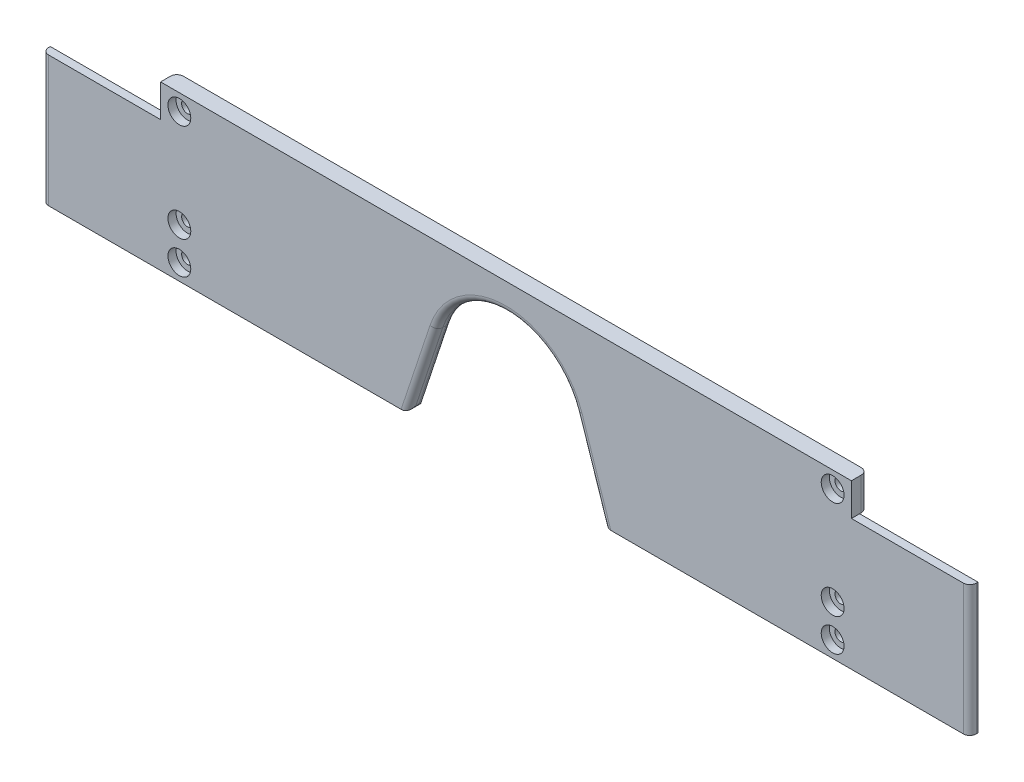
SolidWorks part; units mm, degrees
ref_plane "Front Plane" through (0, 0, 0) normal (0, 0, 1) x (1, 0, 0)
ref_plane "Top Plane" through (0, 0, 0) normal (0, 1, 0) x (1, 0, 0)
ref_plane "Right Plane" through (0, 0, 0) normal (1, 0, 0) x (0, 0, -1)
sketch "Sketch1" plane through (0, 0, 0) normal (0, 0, 1) x (1, 0, 0)
  line L0 (0, 31.75) -> (0, -31.75) construction
  line L1 (-134.3025, -31.75) -> (134.3025, -31.75)
  line L2 (-134.3025, -31.75) -> (-134.3025, 31.75)
  line L3 (-134.3025, 31.75) -> (134.3025, 31.75)
  line L4 (134.3025, -31.75) -> (134.3025, 31.75)
  line L5 (-134.3025, -31.75) -> (134.3025, 31.75) construction
  line L6 (-134.3025, 31.75) -> (134.3025, -31.75) construction
  circle A0 centre (-127, 25.4) radius 2.286
  circle A1 centre (-127, -12.7) radius 2.286
  circle A2 centre (-127, -25.4) radius 2.286
  circle A3 centre (-127, -25.4) radius 2.286 construction
  circle A4 centre (127, 25.4) radius 2.286
  circle A5 centre (127, -12.7) radius 2.286
  circle A6 centre (127, -25.4) radius 2.286
  point P0 (0, 0)
  dimension "D1" = 63.5
  dimension "D2" = 268.605
extrude "Boss-Extrude1" add sketch "Sketch1" along normal blind 3.175
sketch "Sketch2" plane through (0, 0, 3.175) normal (0, 0, 1) x (1, 0, 0)
  line L0 (134.3025, 31.75) -> (-134.3025, 31.75) construction
  line L1 (-180.34, -31.75) -> (180.34, -31.75)
  line L2 (-180.34, -31.75) -> (-180.34, 31.75)
  line L3 (-180.34, 31.75) -> (180.34, 31.75)
  line L4 (180.34, -31.75) -> (180.34, 31.75)
  line L5 (-180.34, -31.75) -> (180.34, 31.75) construction
  line L6 (-180.34, 31.75) -> (180.34, -31.75) construction
  line L7 (0, 31.75) -> (0, -31.75) construction
  circle A0 centre (-127, 25.4) radius 4.445
  circle A1 centre (-127, -12.7) radius 4.445
  circle A2 centre (-127, -25.4) radius 4.445
  circle A3 centre (127, 25.4) radius 4.445
  circle A4 centre (127, -12.7) radius 4.445
  circle A5 centre (127, -25.4) radius 4.445
  point P0 (0, 0)
  dimension "D2" = 8.89
  dimension "D1" = 360.68
extrude "Boss-Extrude2" add sketch "Sketch2" along normal blind 3.175
sketch "Sketch3" plane through (0, 0, 0) normal (0, 0, -1) x (-1, 0, 0)
  line L0 (-134.3025, -31.75) -> (-134.3025, 31.75) construction
  line L1 (-134.3025, 19.05) -> (-121.6025, 19.05)
  line L2 (-134.3025, 19.05) -> (-134.3025, -6.35)
  line L3 (-134.3025, -6.35) -> (-121.6025, -6.35)
  line L4 (-121.6025, 19.05) -> (-121.6025, -6.35)
  line L5 (-134.3025, 31.75) -> (134.3025, 31.75) construction
  line L6 (0, 31.75) -> (0, -31.75) construction
  line L7 (134.3025, -31.75) -> (-134.3025, -31.75) construction
  line L8 (121.6025, 19.05) -> (121.6025, -6.35)
  line L9 (134.3025, -6.35) -> (121.6025, -6.35)
  line L10 (134.3025, 19.05) -> (134.3025, -6.35)
  line L11 (134.3025, 19.05) -> (121.6025, 19.05)
  dimension "D1" = 12.7
  dimension "D2" = 25.4
  dimension "D3" = 12.7
extrude "Cut-Extrude1" cut sketch "Sketch3" against normal up to surface (3.175 mm away) up to face at (157.3212, 0, 3.175)
fillet "Fillet1" radius 2.54 9 edges at (180.34, 0, 6.35) (-180.34, 0, 6.35) (-134.3025, 25.4, 0) (134.3025, -19.05, 0) (134.3025, 25.4, 0) (-121.6025, -6.35, 1.5875) (-121.6025, 19.05, 1.5875) (121.6025, -6.35, 1.5875) (121.6025, 19.05, 1.5875)
sketch "Sketch5" plane through (0, 0, 0) normal (0, 0, -1) x (-1, 0, 0)
  line L0 (-27.1243, 1.369) -> (-38.1, -31.75)
  line L1 (-38.1, -31.75) -> (38.1, -31.75)
  line L2 (38.1, -31.75) -> (27.1243, 1.369)
  line L3 (134.3025, -31.75) -> (-131.7625, -31.75) construction
  arc A2 (27.1243, 1.369) -> (-27.1243, 1.369) centre (0, -7.62) ccw
  dimension "D1" = 57.15
  dimension "D2" = 7.62
  dimension "D3" = 76.2
  dimension "D4" = 38.1
extrude "Cut-Extrude2" cut sketch "Sketch5" against normal through all
fillet "Fillet2" radius 2.54 8 edges at (0, 20.955, 6.35) (-32.6122, -15.1905, 6.35) (-38.1, -31.75, 3.175) (32.6122, -15.1905, 6.35) (38.1, -31.75, 3.175) (0, 20.955, 0) (32.6122, -15.1905, 0) (-32.6122, -15.1905, 0)
sketch "Sketch6" plane through (0, 0, 3.175) normal (0, 0, -1) x (-1, 0, 0)
  line L0 (0, 0) -> (0, 31.75) construction
  line L1 (-180.34, 31.75) -> (-134.3025, 31.75)
  line L2 (-180.34, 31.75) -> (-180.34, 19.05)
  line L3 (-180.34, 19.05) -> (-134.3025, 19.05)
  line L4 (-134.3025, 31.75) -> (-134.3025, 19.05)
  line L5 (-131.7625, 31.75) -> (131.7625, 31.75) construction
  line L6 (134.3025, 31.75) -> (134.3025, 19.05)
  line L7 (180.34, 19.05) -> (134.3025, 19.05)
  line L8 (180.34, 31.75) -> (134.3025, 31.75)
  line L9 (180.34, 31.75) -> (180.34, 19.05)
  line L10 (-134.3025, 19.05) -> (-134.3025, 31.75) construction
  line L11 (-180.34, 31.75) -> (-134.3025, 31.75) construction
  point P14 (-134.3025, 31.75)
  dimension "D1" = 12.7
extrude "Cut-Extrude3" cut sketch "Sketch6" against normal through all
